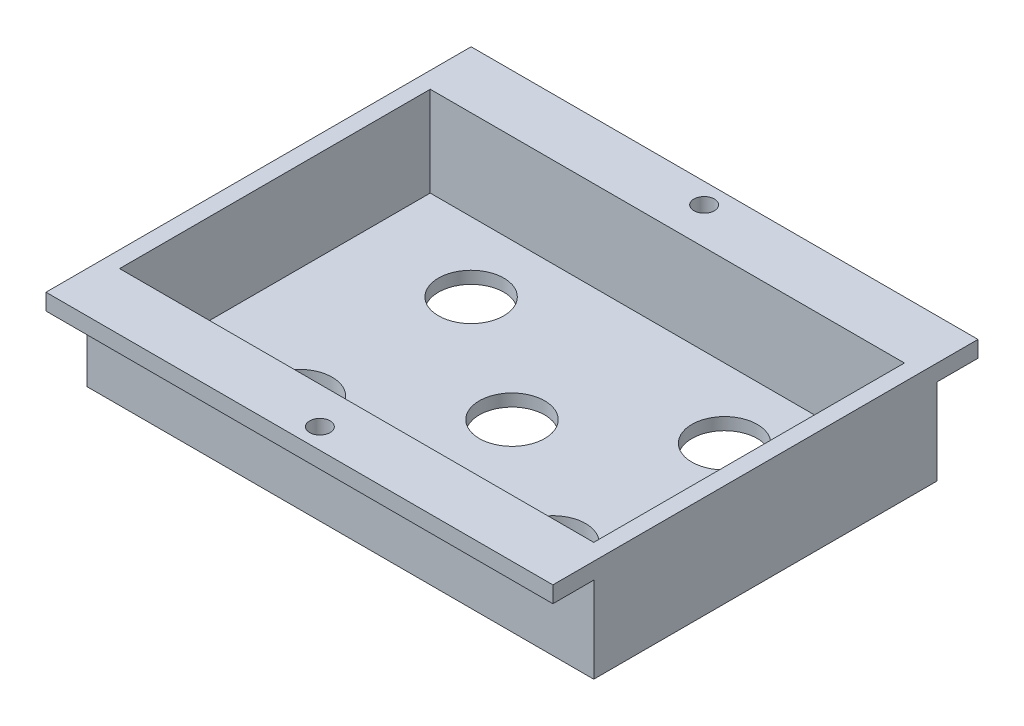
SolidWorks part; units mm, degrees
ref_plane "Front Plane" through (0, 0, 0) normal (0, 0, 1) x (1, 0, 0)
ref_plane "Top Plane" through (0, 0, 0) normal (0, 1, 0) x (1, 0, 0)
ref_plane "Right Plane" through (0, 0, 0) normal (1, 0, 0) x (0, 0, -1)
sketch "Sketch1" plane through (0, 0, 0) normal (0, 1, 0) x (1, 0, 0)
  line L1 (-62, -42) -> (62, -42)
  line L2 (-62, -42) -> (-62, 42)
  line L3 (-62, 42) -> (62, 42)
  line L4 (62, -42) -> (62, 42)
  line L5 (-62, -42) -> (62, 42) construction
  line L6 (-62, 42) -> (62, -42) construction
  point P0 (0, 0)
  dimension "D1" = 84
  dimension "D2" = 124
extrude "Boss-Extrude1" add sketch "Sketch1" along normal blind 25
sketch "Sketch2" plane through (0, 25, 0) normal (0, 1, 0) x (1, 0, 0)
  line L22 (58, -38) -> (58, 38)
  line L23 (-58, -38) -> (58, -38)
  line L24 (-58, 38) -> (-58, -38)
  line L25 (58, 38) -> (-58, 38)
  line L26 (58, -38) -> (58, 38)
  line L27 (-58, -38) -> (58, -38)
  line L28 (-58, 38) -> (-58, -38)
  line L29 (58, 38) -> (-58, 38)
  dimension "D1" = 4
extrude "Cut-Extrude1" cut sketch "Sketch2" against normal blind 22
sketch "Sketch3" plane through (0, 3, 0) normal (0, 1, 0) x (1, 0, 0)
  line L1 (-62, -42) -> (62, -42) construction
  line L2 (62, 42) -> (-62, 42) construction
  line L3 (62, -42) -> (62, 42) construction
  line L4 (-62, 42) -> (-62, -42) construction
  circle A0 centre (0, 0) radius 8
  circle A1 centre (-31, 21) radius 8
  circle A2 centre (-31, -21) radius 8
  circle A3 centre (31, 21) radius 8
  circle A4 centre (31, -21) radius 8
  dimension "D1" = 21
  dimension "D2" = 21
  dimension "D3" = 21
  dimension "D4" = 21
  dimension "D5" = 31
  dimension "D6" = 31
  dimension "D7" = 31
  dimension "D8" = 31
extrude "Cut-Extrude2" cut sketch "Sketch3" against normal through all
sketch "Sketch4" plane through (0, 0, 42) normal (0, 0, 1) x (1, 0, 0)
  line L0 (62, 25) -> (62, 0) construction
  line L1 (-62, 25) -> (62, 25)
  line L2 (-62, 25) -> (-62, 21)
  line L3 (-62, 21) -> (62, 21)
  line L4 (62, 25) -> (62, 21)
  dimension "D1" = 4
extrude "Boss-Extrude2" add sketch "Sketch4" along normal blind 10
sketch "Sketch5" plane through (0, 0, -42) normal (0, 0, -1) x (-1, 0, 0)
  line L1 (-62, 25) -> (62, 25)
  line L2 (-62, 25) -> (-62, 21)
  line L3 (-62, 21) -> (62, 21)
  line L4 (62, 25) -> (62, 21)
extrude "Boss-Extrude3" add sketch "Sketch5" along normal blind 10
sketch "Sketch6" plane through (0, 25, 0) normal (0, 1, 0) x (1, 0, 0)
  line L0 (-62, 52) -> (-62, -52) construction
  line L4 (-62, 52) -> (62, 52) construction
  line L5 (62, -52) -> (-62, -52) construction
  circle A4 centre (0, 47) radius 2.5
  circle A5 centre (0, -47) radius 2.5
  dimension "D1" = 5
  dimension "D4" = 5
  dimension "D5" = 5
  dimension "D2" = 5
  dimension "D3" = 62
extrude "Cut-Extrude3" cut sketch "Sketch6" against normal through all
